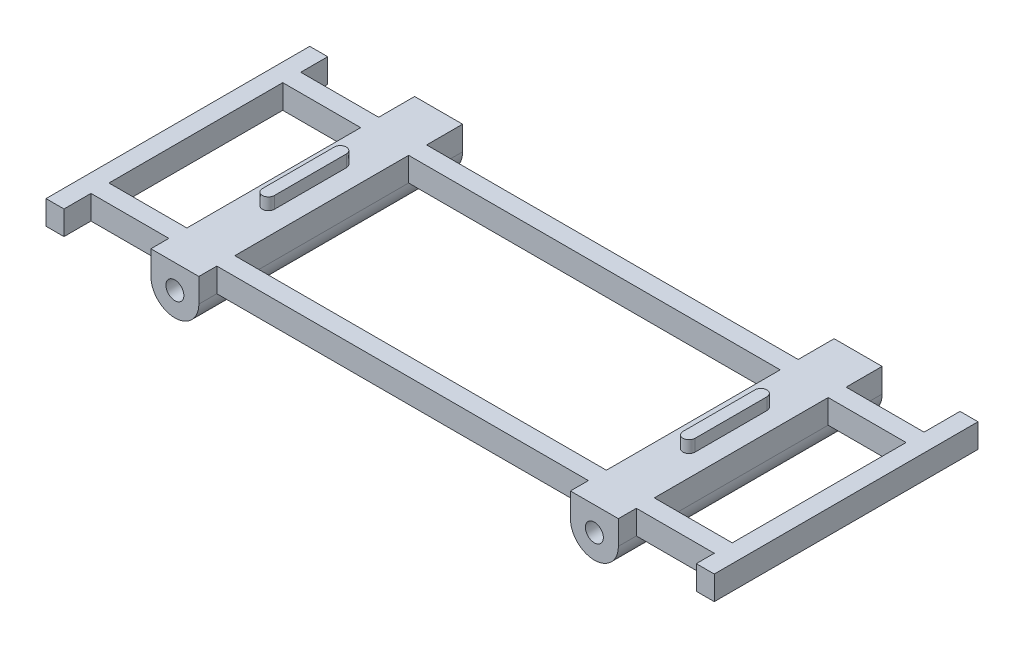
SolidWorks part; units mm, degrees
ref_plane "Front Plane" through (0, 0, 0) normal (0, 0, 1) x (1, 0, 0)
ref_plane "Top Plane" through (0, 0, 0) normal (0, 1, 0) x (1, 0, 0)
ref_plane "Right Plane" through (0, 0, 0) normal (1, 0, 0) x (0, 0, -1)
sketch "Sketch1" plane through (0, 0, 0) normal (0, 1, 0) x (1, 0, 0)
  line L0 (0, 0) -> (614.9543, 0) construction
  line L2 (80.0054, 102.5) -> (65.0054, 102.5)
  line L3 (80.0054, 102.5) -> (80.0054, -117.5)
  line L4 (80.0054, -117.5) -> (65.0054, -117.5)
  line L5 (65.0054, 102.5) -> (65.0054, -117.5)
  line L6 (599.9543, 110) -> (614.9543, 110)
  line L7 (599.9543, 110) -> (599.9543, -110)
  line L8 (599.9543, -110) -> (614.9543, -110)
  line L9 (614.9543, 110) -> (614.9543, -110)
  line L10 (80.0054, 80) -> (599.9543, 80)
  line L11 (80.0054, 80) -> (80.0054, 65)
  line L12 (80.0054, 65) -> (599.9543, 65)
  line L13 (599.9543, 80) -> (599.9543, 65)
  line L14 (80.0054, -95) -> (599.9543, -95)
  line L15 (80.0054, -95) -> (80.0054, -80)
  line L16 (80.0054, -80) -> (599.9543, -80)
  line L17 (599.9543, -95) -> (599.9543, -80)
  dimension "D1" = 550
  dimension "D2" = 15
  dimension "D3" = 15
  dimension "D4" = 15
  dimension "D5" = 220
  dimension "D6" = 220
  dimension "D7" = 160
  dimension "D8" = 15
  dimension "D9" = 22.5
  dimension "D10" = 15
extrude "Boss-Extrude1" add sketch "Sketch1" against normal blind 20 contours L3 L12 L7 L10 | L0 L5 L4 L3 | L16 L17 L14 L15
sketch "Sketch2" plane through (0, 0, 0) normal (0, 0, 1) x (1, 0, 0)
  line L0 (80.0054, 0) -> (599.9543, 0) construction
  line L1 (145.0054, 0) -> (185.0054, 0)
  line L2 (145.0054, 0) -> (145.0054, -20)
  line L4 (185.0054, 0) -> (185.0054, -20)
  line L5 (80.0054, -20) -> (599.9543, -20) construction
  line L7 (494.9543, 0) -> (534.9543, 0)
  line L8 (494.9543, 0) -> (494.9543, -20)
  line L10 (534.9543, 0) -> (534.9543, -20)
  arc A0 (145.0054, -20) -> (185.0054, -20) centre (165.0054, -20) ccw
  arc A1 (494.9543, -20) -> (534.9543, -20) centre (514.9543, -20) ccw
  dimension "D1" = 20
  dimension "D2" = 20
  dimension "D3" = 100
  dimension "D4" = 40
  dimension "D5" = 100
  dimension "D6" = 40
extrude "Boss-Extrude3" add sketch "Sketch2" along normal mid plane 220
sketch "Sketch3" plane through (0, 0, 110) normal (0, 0, 1) x (1, 0, 0)
  circle A0 centre (165.0054, -20) radius 7.5
  circle A1 centre (514.9543, -20) radius 7.5
  dimension "D1" = 15
  dimension "D2" = 15
extrude "Cut-Extrude1" cut sketch "Sketch3" against normal through all
sketch "Sketch4" plane through (0, 0, 0) normal (0, 1, 0) x (1, 0, 0)
  line L0 (0, 0) -> (631.5009, 0) construction
  line L1 (163.022, -30) -> (163.022, 30) construction
  line L2 (158.022, -30) -> (158.022, 30)
  line L3 (168.022, -30) -> (168.022, 30)
  line L4 (513.8803, -30) -> (513.8803, 30) construction
  line L5 (508.8803, -30) -> (508.8803, 30)
  line L6 (518.8803, -30) -> (518.8803, 30)
  arc A0 (158.022, -30) -> (168.022, -30) centre (163.022, -30) ccw
  arc A1 (168.022, 30) -> (158.022, 30) centre (163.022, 30) ccw
  arc A2 (508.8803, -30) -> (518.8803, -30) centre (513.8803, -30) ccw
  arc A3 (518.8803, 30) -> (508.8803, 30) centre (513.8803, 30) ccw
  point P5 (163.022, 0)
  point P11 (513.8803, 0)
  dimension "D3" = 5
  dimension "D4" = 5
  dimension "D1" = 60
  dimension "D2" = 60
extrude "Boss-Extrude5" add sketch "Sketch4" along normal blind 10
